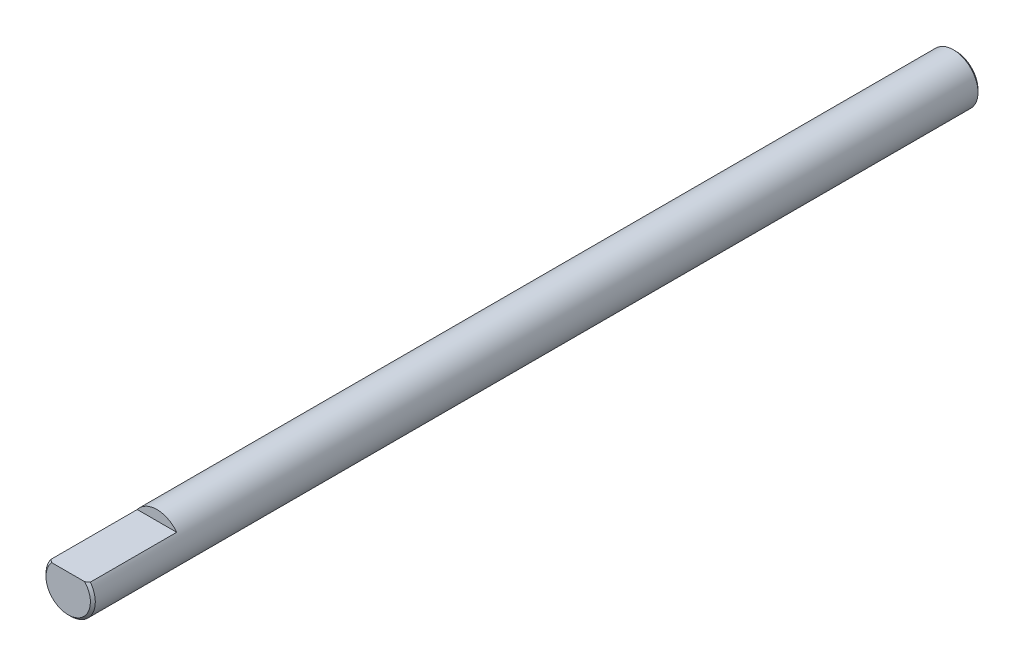
SolidWorks part; units mm, degrees
ref_plane "Front Plane" through (0, 0, 0) normal (0, 0, 1) x (1, 0, 0)
ref_plane "Top Plane" through (0, 0, 0) normal (0, 1, 0) x (1, 0, 0)
ref_plane "Right Plane" through (0, 0, 0) normal (1, 0, 0) x (0, 0, -1)
sketch "Sketch1" plane through (0, 0, 0) normal (0, 0, 1) x (1, 0, 0)
  circle A0 centre (0, 0) radius 2.5
  dimension "D1" = 5
extrude "Boss-Extrude1" add sketch "Sketch1" along normal blind 90
sketch "Sketch2" plane through (0, 0, 90) normal (0, 0, 1) x (1, 0, 0)
  line L1 (-4.0228, 2.5) -> (3.9197, 2.5)
  line L2 (-4.0228, 2.5) -> (-4.0228, 1.5)
  line L3 (-4.0228, 1.5) -> (3.9197, 1.5)
  line L4 (3.9197, 2.5) -> (3.9197, 1.5)
  dimension "D1" = 1.5
  dimension "D2" = 1
extrude "Cut-Extrude1" cut sketch "Sketch2" against normal blind 9
chamfer "Chamfer1" distance 0.25 angle 45 2 edges at (2.5, 0, 0) (0, -2.5, 90)
